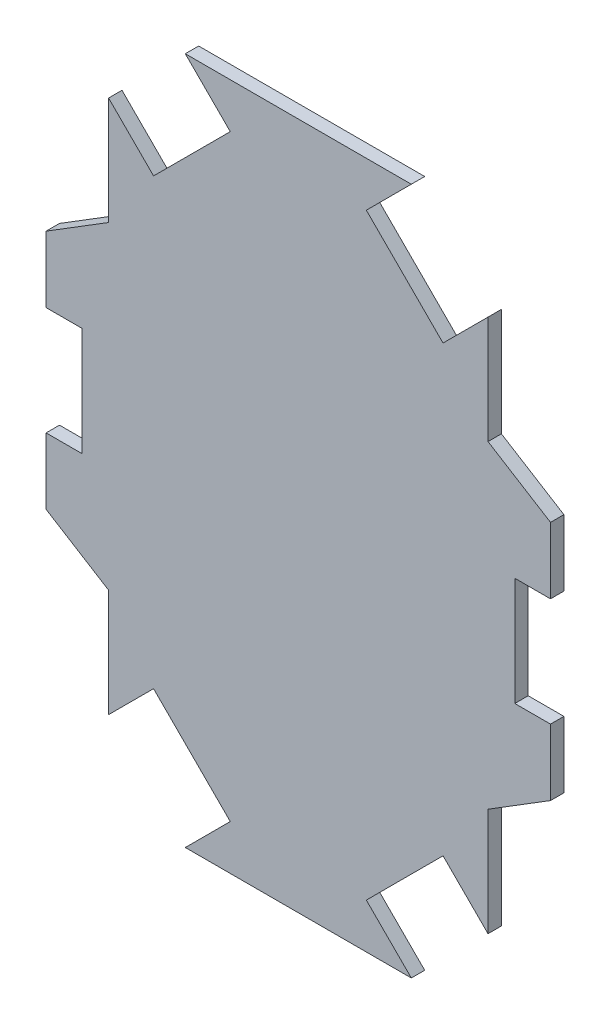
SolidWorks part; units mm, degrees
ref_plane "前视基准面" through (0, 0, 0) normal (0, 0, 1) x (1, 0, 0)
ref_plane "上视基准面" through (0, 0, 0) normal (0, 1, 0) x (1, 0, 0)
ref_plane "右视基准面" through (0, 0, 0) normal (1, 0, 0) x (0, 0, -1)
sketch "草图1" plane through (0, 0, 0) normal (0, 0, 1) x (1, 0, 0)
  line L1 (0, 0) -> (85, 0)
  line L2 (0, 0) -> (0, -154)
  line L3 (0, -154) -> (85, -154)
  line L4 (85, 0) -> (85, -154)
  dimension "D1" = 85
  dimension "D2" = 154
extrude "凸台-拉伸1" add sketch "草图1" along normal blind 3
sketch "草图2" plane through (0, 0, 3) normal (0, 0, 1) x (1, 0, 0)
  line L0 (0, 0) -> (13.4582, -13.4582) construction
  line L1 (0, -77) -> (95.6915, -77) construction
  line L2 (0, 0) -> (0, -154) construction
  line L3 (42.5, 0) -> (42.5, -122.2721) construction
  line L4 (85, 0) -> (0, 0) construction
  line L6 (10.0763, -27.259) -> (-21.3193, 4.1366)
  line L7 (-21.3193, 4.1366) -> (-4.1366, 21.3193)
  line L8 (-4.1366, 21.3193) -> (27.259, -10.0763)
  line L10 (10.0763, -27.259) -> (27.259, -10.0763)
  line L11 (-21.3193, -158.1366) -> (-4.1366, -175.3193)
  line L12 (-4.1366, -175.3193) -> (27.259, -143.9237)
  line L13 (10.0763, -126.741) -> (27.259, -143.9237)
  line L14 (10.0763, -126.741) -> (-21.3193, -158.1366)
  line L15 (74.9237, -126.741) -> (106.3193, -158.1366)
  line L16 (106.3193, -158.1366) -> (89.1366, -175.3193)
  line L17 (89.1366, -175.3193) -> (57.741, -143.9237)
  line L18 (74.9237, -126.741) -> (57.741, -143.9237)
  line L19 (74.9237, -27.259) -> (57.741, -10.0763)
  line L20 (89.1366, 21.3193) -> (57.741, -10.0763)
  line L21 (106.3193, 4.1366) -> (89.1366, 21.3193)
  line L22 (74.9237, -27.259) -> (106.3193, 4.1366)
  line L23 (42.5, -77) -> (66.3324, -18.6676) construction
  line L24 (42.5, -77) -> (102.5, -77) construction
  line L25 (85, -41.3346) -> (99, -50.0114)
  line L26 (85, -154) -> (85, 0) construction
  line L27 (99, -50.0114) -> (99, -103.9886)
  line L28 (99, -103.9886) -> (85, -112.6654)
  line L29 (85, -41.3346) -> (85, -112.6654)
  line L30 (0, -41.3346) -> (-14, -50.0114)
  line L31 (0, -41.3346) -> (0, -112.6654)
  line L32 (-14, -50.0114) -> (-14, -103.9886)
  line L33 (-14, -103.9886) -> (0, -112.6654)
  point P27 (42.5, -77)
  dimension "D1" = 45
  dimension "D2" = 24.3
  dimension "D3" = 44.4
  dimension "D4" = 18
  dimension "D5" = 60
  dimension "D6" = 14
extrude "切除-拉伸2" cut sketch "草图2" against normal blind 58
sketch "草图3" plane through (0, 0, 3) normal (0, 0, 1) x (1, 0, 0)
  line L0 (85, -41.3346) -> (99, -50.0114) construction
  line L1 (99, -50.0114) -> (99, -103.9886) construction
  line L2 (85, -41.3346) -> (85, -112.6654) construction
  line L3 (99, -103.9886) -> (85, -112.6654) construction
  line L4 (-14, -103.9886) -> (0, -112.6654) construction
  line L5 (0, -41.3346) -> (0, -112.6654) construction
  line L6 (-14, -50.0114) -> (-14, -103.9886) construction
  line L7 (0, -41.3346) -> (-14, -50.0114) construction
  line L8 (85, -41.3346) -> (99, -50.0114)
  line L9 (99, -50.0114) -> (99, -103.9886)
  line L10 (85, -41.3346) -> (85, -112.6654)
  line L11 (99, -103.9886) -> (85, -112.6654)
  line L12 (-14, -103.9886) -> (0, -112.6654)
  line L13 (0, -41.3346) -> (0, -112.6654)
  line L14 (-14, -50.0114) -> (-14, -103.9886)
  line L15 (0, -41.3346) -> (-14, -50.0114)
extrude "凸台-拉伸2" add sketch "草图3" against normal up to vertex (3 mm away)
sketch "草图4" plane through (0, 0, 3) normal (0, 0, 1) x (1, 0, 0)
  line L0 (0, -77) -> (95.6915, -77) construction
  line L1 (91, -64.85) -> (135.4, -64.85)
  line L2 (91, -64.85) -> (91, -89.15)
  line L3 (91, -89.15) -> (135.4, -89.15)
  line L4 (135.4, -64.85) -> (135.4, -89.15)
  line L5 (99, -77) -> (27.7144, -77) construction
  line L6 (99, -50.0114) -> (99, -103.9886) construction
  line L7 (42.5, 0) -> (42.5, -50.6182) construction
  line L8 (42.5, 0) -> (42.5, -122.2721) construction
  line L9 (-6, -64.85) -> (-6, -89.15)
  line L10 (-6, -89.15) -> (-50.4, -89.15)
  line L11 (-50.4, -64.85) -> (-50.4, -89.15)
  line L12 (-6, -64.85) -> (-50.4, -64.85)
  dimension "D1" = 24.3
  dimension "D2" = 44.4
  dimension "D3" = 8
extrude "切除-拉伸3" cut sketch "草图4" against normal blind 58
